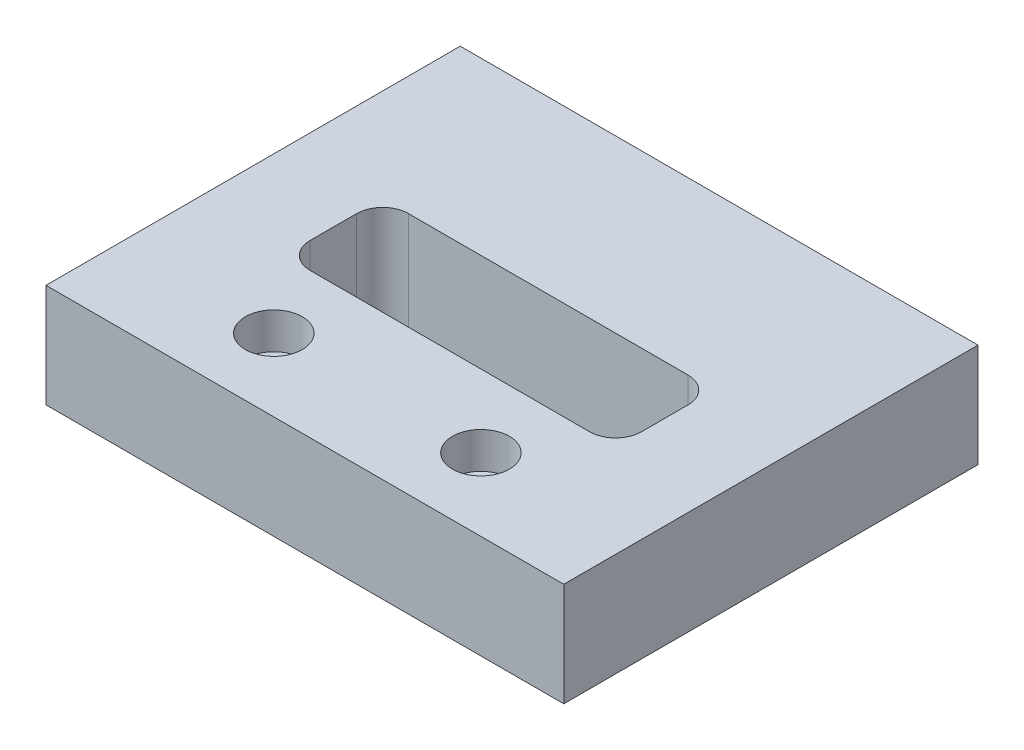
SolidWorks part; units mm, degrees
ref_plane "前视基准面" through (0, 0, 0) normal (0, 0, 1) x (1, 0, 0)
ref_plane "上视基准面" through (0, 0, 0) normal (0, 1, 0) x (1, 0, 0)
ref_plane "右视基准面" through (0, 0, 0) normal (1, 0, 0) x (0, 0, -1)
sketch "草图1" plane through (0, 0, 0) normal (0, 1, 0) x (1, 0, 0)
  line L1 (-50, -40) -> (50, -40)
  line L2 (-50, -40) -> (-50, 40)
  line L3 (-50, 40) -> (50, 40)
  line L4 (50, -40) -> (50, 40)
  line L5 (0, 40) -> (0, -40) construction
  line L6 (-50, 0) -> (50, 0) construction
  line L7 (-32, -12) -> (32, -12)
  line L8 (-32, -12) -> (-32, 7)
  line L9 (-32, 7) -> (32, 7)
  line L10 (32, -12) -> (32, 7)
  point P0 (0, 0)
  dimension "D1" = 100
  dimension "D2" = 80
  dimension "D3" = 18
  dimension "D4" = 82
  dimension "D5" = 28
  dimension "D6" = 47
extrude "凸台-拉伸1" add sketch "草图1" along normal blind 20
fillet "圆角1" radius 5 4 edges at (32, 10, 12) (-32, 10, 12) (32, 10, -7) (-32, 10, -7)
hole_wizard "孔1" positions "草图2" profile "草图3" legacy
sketch "草图2" plane through (0, 20, 0) normal (0, 1, 0) x (1, 0, 0)
  line L0 (-50, -40) -> (50, -40) construction
  line L1 (50, -40) -> (50, 40) construction
  point P0 (20, -26)
  point P2 (-20, -26)
  point P13 (-11.4883, -40)
  point P14 (0, 0)
  dimension "D1" = 14
  dimension "D2" = 30
  dimension "D3" = 70
  dimension "D4" = 14
sketch "草图3" plane through (20, 20, 26) normal (1, 0, 0) x (0, 0, 1)
  line L0 (0, 0) -> (0, 100)
  line L1 (0, 100) -> (3.2, 100)
  line L2 (3.2, 100) -> (3.2, 7)
  line L3 (3.2, 7) -> (5.5, 7)
  line L4 (5.5, 7) -> (5.5, 0)
  line L5 (5.5, 0) -> (0, 0)
  line L6 (0, -6.13) -> (0, 109.2824) construction
  line L7 (-3.2, 7) -> (-5.5, 7) construction
  line L8 (0, 100) -> (-3.2, 100) construction
  dimension "直径" = 6.4
  dimension "深度" = 100
  dimension "沉头坑直径" = 11
  dimension "沉头坑深度" = 7
  dimension "导头角度" = 180
